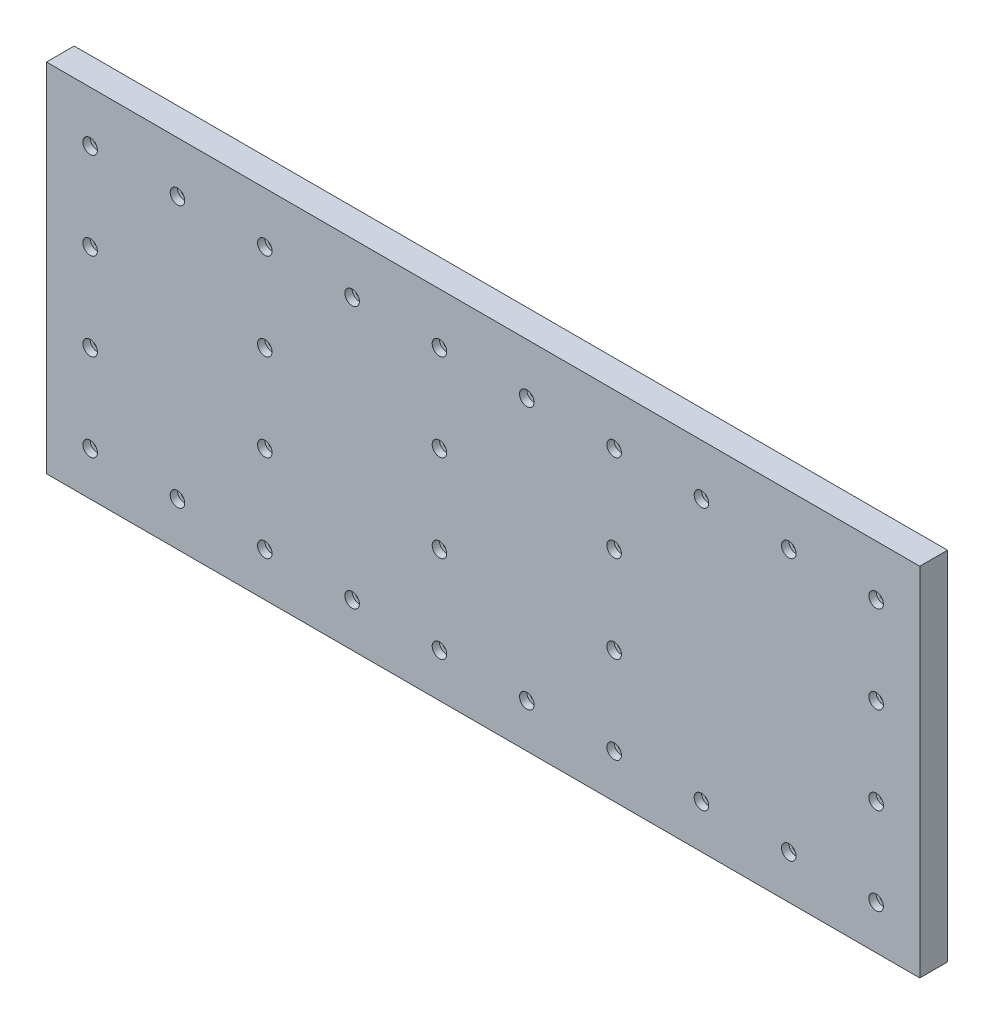
SolidWorks part; units mm, degrees
ref_plane "Front Plane" through (0, 0, 0) normal (0, 0, 1) x (1, 0, 0)
ref_plane "Top Plane" through (0, 0, 0) normal (0, 1, 0) x (1, 0, 0)
ref_plane "Right Plane" through (0, 0, 0) normal (1, 0, 0) x (0, 0, -1)
sketch "Sketch1" plane through (0, 0, 0) normal (0, 0, 1) x (1, 0, 0)
  line L1 (300, 5) -> (-300, 5)
  line L2 (300, 5) -> (300, 250)
  line L3 (300, 250) -> (-300, 250)
  line L4 (-300, 5) -> (-300, 250)
  dimension "D1" = 245
  dimension "D2" = 600
extrude "Boss-Extrude1" add sketch "Sketch1" along normal blind 19.05
sketch "Sketch2" plane through (0, 0, 19.05) normal (0, 0, 1) x (1, 0, 0)
  circle A0 centre (270, 35) radius 2.5 construction
  circle A1 centre (210, 35) radius 2.5 construction
  circle A2 centre (150, 35) radius 2.5 construction
  circle A3 centre (90, 35) radius 2.5 construction
  circle A4 centre (30, 35) radius 2.5 construction
  circle A5 centre (-30, 35) radius 2.5 construction
  circle A6 centre (-90, 35) radius 2.5 construction
  circle A7 centre (-150, 35) radius 2.5 construction
  circle A8 centre (-210, 35) radius 2.5 construction
  circle A9 centre (-270, 35) radius 2.5 construction
  circle A10 centre (-270, 215) radius 2.5 construction
  circle A11 centre (-210, 215) radius 2.5 construction
  circle A12 centre (-150, 215) radius 2.5 construction
  circle A13 centre (-90, 215) radius 2.5 construction
  circle A14 centre (-30, 215) radius 2.5 construction
  circle A15 centre (30, 215) radius 2.5 construction
  circle A16 centre (90, 215) radius 2.5 construction
  circle A17 centre (150, 215) radius 2.5 construction
  circle A18 centre (210, 215) radius 2.5 construction
  circle A19 centre (270, 215) radius 2.5 construction
  circle A20 centre (270, 35) radius 2.5
  circle A21 centre (210, 35) radius 2.5
  circle A22 centre (150, 35) radius 2.5
  circle A23 centre (90, 35) radius 2.5
  circle A24 centre (30, 35) radius 2.5
  circle A25 centre (-30, 35) radius 2.5
  circle A26 centre (-90, 35) radius 2.5
  circle A27 centre (-150, 35) radius 2.5
  circle A28 centre (-210, 35) radius 2.5
  circle A29 centre (-270, 35) radius 2.5
  circle A30 centre (-270, 215) radius 2.5
  circle A31 centre (-210, 215) radius 2.5
  circle A32 centre (-150, 215) radius 2.5
  circle A33 centre (-90, 215) radius 2.5
  circle A34 centre (-30, 215) radius 2.5
  circle A35 centre (30, 215) radius 2.5
  circle A36 centre (90, 215) radius 2.5
  circle A37 centre (150, 215) radius 2.5
  circle A38 centre (210, 215) radius 2.5
  circle A39 centre (270, 215) radius 2.5
  circle A40 centre (-150, 95) radius 2.5
  circle A45 centre (90, 95) radius 2.5
  circle A46 centre (-30, 95) radius 2.5
  circle A47 centre (270, 95) radius 2.5
  circle A49 centre (-270, 95) radius 2.5
  circle A50 centre (-30, 155) radius 2.5
  circle A51 centre (-270, 155) radius 2.5
  circle A52 centre (270, 155) radius 2.5
  circle A55 centre (90, 155) radius 2.5
  circle A57 centre (-150, 155) radius 2.5
hole_wizard "CBORE for M5 SHCS1" positions "Sketch3" profile "Sketch4" counterbore size "M5" standard "ANSI Metric"
sketch "Sketch3" plane through (0, 0, 19.05) normal (0, 0, 1) x (1, 0, 0)
  point P0 (-270, 215)
  point P3 (-210, 215)
  point P6 (-150, 215)
  point P9 (-90, 215)
  point P12 (-30, 215)
  point P15 (30, 215)
  point P18 (90, 215)
  point P21 (150, 215)
  point P24 (210, 215)
  point P27 (270, 215)
  point P30 (270, 155)
  point P33 (270, 95)
  point P36 (90, 155)
  point P39 (90, 95)
  point P42 (-30, 155)
  point P45 (-30, 95)
  point P48 (-150, 155)
  point P51 (-270, 155)
  point P54 (-270, 95)
  point P57 (-150, 95)
  point P60 (-270, 35)
  point P63 (-210, 35)
  point P66 (-150, 35)
  point P69 (-90, 35)
  point P72 (-30, 35)
  point P75 (30, 35)
  point P78 (90, 35)
  point P81 (150, 35)
  point P84 (210, 35)
  point P87 (270, 35)
sketch "Sketch4" plane through (-270, 215, 19.05) normal (1, 0, 0) x (0, -1, 0)
  line L0 (0, 0) -> (0, 30)
  line L1 (0, 30) -> (2.5, 28.4978)
  line L2 (2.5, 28.4978) -> (2.5, 5)
  line L3 (2.5, 5) -> (5, 5)
  line L4 (5, 5) -> (5, 0)
  line L5 (5, 0) -> (0, 0)
  line L10 (0, 30) -> (-2.5, 28.4978) construction
  line L11 (0, -6.35) -> (0, 107.95) construction
  dimension "Hole Dia." = 5
  dimension "Hole Depth" = 30
  dimension "C'Bore Dia." = 10
  dimension "C'Bore Depth" = 5
  dimension "Drill Angle" = 118
